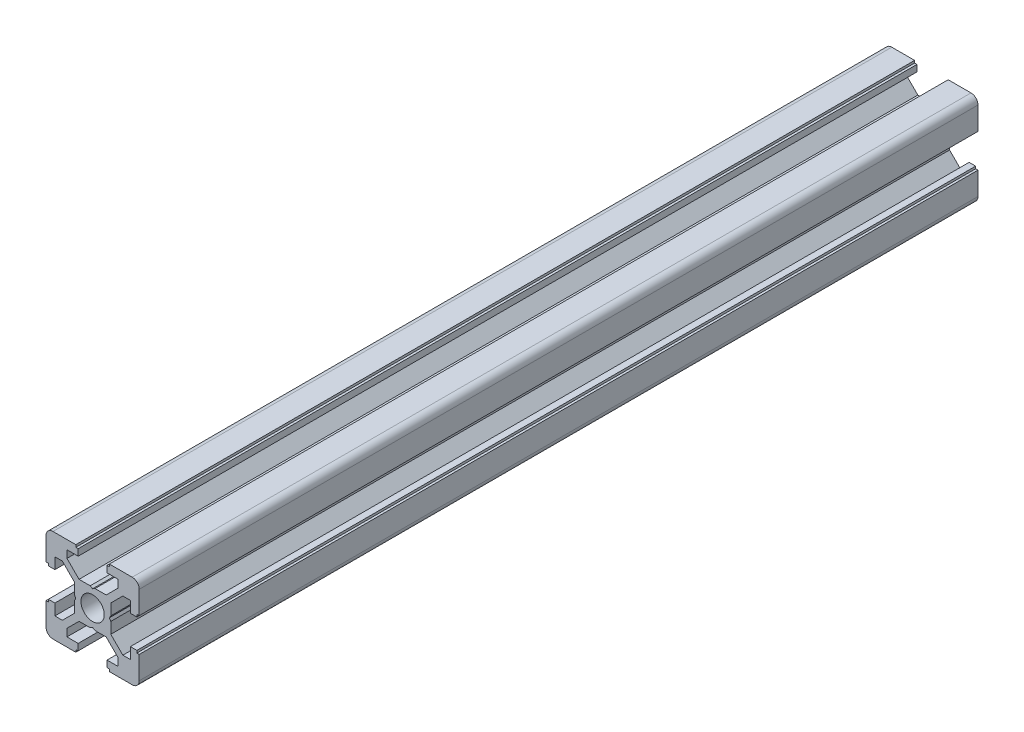
SolidWorks part; units mm, degrees
ref_plane "前视基准面" through (0, 0, 0) normal (0, 0, 1) x (1, 0, 0)
ref_plane "上视基准面" through (0, 0, 0) normal (0, 1, 0) x (1, 0, 0)
ref_plane "右视基准面" through (0, 0, 0) normal (1, 0, 0) x (0, 0, -1)
sketch "草图28" plane through (0, 0, 0) normal (0, 0, 1) x (1, 0, 0)
  line B0 (0, 11.0182) -> (0, -11.0182) construction
  line B1 (-11.0182, 0) -> (11.0182, 0) construction
  line B2 (-3.9, -0.5196) -> (-3.9, -2.9101)
  line B3 (-3.9, -2.9101) -> (-6.4899, -5.5)
  line B4 (-6.4899, -5.5) -> (-8.1, -5.5)
  line B5 (-8.1, -5.5) -> (-8.1, -3.1)
  line B6 (-8.1, -3.1) -> (-9.5, -3.1)
  line B7 (-9.5, -3.1) -> (-9.5, -3.6)
  line B8 (-9.5, -3.6) -> (-10, -3.6)
  line B9 (-10, -3.6) -> (-10, -8.5)
  line B10 (-8.5, -10) -> (-3.6, -10)
  line B11 (-3.6, -10) -> (-3.6, -9.5)
  line B12 (-3.6, -9.5) -> (-3.1, -9.5)
  line B13 (-3.1, -9.5) -> (-3.1, -8.1)
  line B14 (-3.1, -8.1) -> (-5.5, -8.1)
  line B15 (-5.5, -8.1) -> (-5.5, -6.4899)
  line B16 (-5.5, -6.4899) -> (-2.9101, -3.9)
  line B17 (-2.9101, -3.9) -> (-0.5196, -3.9)
  line B18 (-0.5196, -3.9) -> (0, -3.6)
  line B19 (0, -3.6) -> (0.5196, -3.9)
  line B20 (0.5196, -3.9) -> (2.9101, -3.9)
  line B21 (2.9101, -3.9) -> (5.5, -6.4899)
  line B22 (5.5, -6.4899) -> (5.5, -8.1)
  line B23 (5.5, -8.1) -> (3.1, -8.1)
  line B24 (3.1, -8.1) -> (3.1, -9.5)
  line B25 (3.1, -9.5) -> (3.6, -9.5)
  line B26 (3.6, -9.5) -> (3.6, -10)
  line B27 (3.6, -10) -> (8.5, -10)
  line B28 (10, -8.5) -> (10, -3.6)
  line B29 (10, -3.6) -> (9.5, -3.6)
  line B30 (9.5, -3.6) -> (9.5, -3.1)
  line B31 (9.5, -3.1) -> (8.1, -3.1)
  line B32 (8.1, -3.1) -> (8.1, -5.5)
  line B33 (8.1, -5.5) -> (6.4899, -5.5)
  line B34 (6.4899, -5.5) -> (3.9, -2.9101)
  line B35 (3.9, -2.9101) -> (3.9, -0.5196)
  line B36 (3.9, -0.5196) -> (3.6, 0)
  line B37 (3.6, 0) -> (3.9, 0.5196)
  line B38 (3.9, 0.5196) -> (3.9, 2.9101)
  line B39 (3.9, 2.9101) -> (6.4899, 5.5)
  line B40 (6.4899, 5.5) -> (8.1, 5.5)
  line B41 (8.1, 5.5) -> (8.1, 3.1)
  line B42 (8.1, 3.1) -> (9.5, 3.1)
  line B43 (9.5, 3.1) -> (9.5, 3.6)
  line B44 (9.5, 3.6) -> (10, 3.6)
  line B45 (10, 3.6) -> (10, 8.5)
  line B46 (8.5, 10) -> (3.6, 10)
  line B47 (3.6, 10) -> (3.6, 9.5)
  line B48 (3.6, 9.5) -> (3.1, 9.5)
  line B49 (3.1, 9.5) -> (3.1, 8.1)
  line B50 (3.1, 8.1) -> (5.5, 8.1)
  line B51 (5.5, 8.1) -> (5.5, 6.4899)
  line B52 (5.5, 6.4899) -> (2.9101, 3.9)
  line B53 (2.9101, 3.9) -> (0.5196, 3.9)
  line B54 (0.5196, 3.9) -> (0, 3.6)
  line B55 (0, 3.6) -> (-0.5196, 3.9)
  line B56 (-0.5196, 3.9) -> (-2.9101, 3.9)
  line B57 (-2.9101, 3.9) -> (-5.5, 6.4899)
  line B58 (-5.5, 6.4899) -> (-5.5, 8.1)
  line B59 (-5.5, 8.1) -> (-3.1, 8.1)
  line B60 (-3.1, 8.1) -> (-3.1, 9.5)
  line B61 (-3.1, 9.5) -> (-3.6, 9.5)
  line B62 (-3.6, 9.5) -> (-3.6, 10)
  line B63 (-3.6, 10) -> (-8.5, 10)
  line B64 (-10, 8.5) -> (-10, 3.6)
  line B65 (-10, 3.6) -> (-9.5, 3.6)
  line B66 (-9.5, 3.6) -> (-9.5, 3.1)
  line B67 (-9.5, 3.1) -> (-8.1, 3.1)
  line B68 (-8.1, 3.1) -> (-8.1, 5.5)
  line B69 (-8.1, 5.5) -> (-6.4899, 5.5)
  line B70 (-6.4899, 5.5) -> (-3.9, 2.9101)
  line B71 (-3.9, 2.9101) -> (-3.9, 0.5196)
  line B72 (-3.9, 0.5196) -> (-3.6, 0)
  line B73 (-3.6, 0) -> (-3.9, -0.5196)
  circle B74 centre (0, 0) radius 2.5
  arc B75 (-10, -8.5) -> (-8.5, -10) centre (-8.5, -8.5) ccw
  arc B76 (8.5, -10) -> (10, -8.5) centre (8.5, -8.5) ccw
  arc B77 (10, 8.5) -> (8.5, 10) centre (8.5, 8.5) ccw
  arc B78 (-8.5, 10) -> (-10, 8.5) centre (-8.5, 8.5) ccw
sketch_block_instance "块1-1"
sketch_block "块1"
extrude "凸台-拉伸1" add sketch "草图28" along normal blind 180
cosmetic thread "装饰螺纹线1" [suppressed] parameters "D1"=15, "D2"=6
cosmetic thread "装饰螺纹线2" [suppressed] parameters "D1"=15, "D2"=6
ref_plane "基准面1" through (0, 0, 180) normal (0, 0, 1) x (1, 0, 0)
ref_plane "基准面2" through (0, 10, 0) normal (0, 1, 0) x (1, 0, 0)
ref_plane "基准面3" through (0, -10, 0) normal (0, 1, 0) x (1, 0, 0)
ref_plane "基准面4" through (10, 0, 0) normal (1, 0, 0) x (0, 0, -1)
ref_plane "基准面5" through (-10, 0, 0) normal (1, 0, 0) x (0, 0, -1)
sketch "草图19" plane through (0, 0, 0) normal (0, 0, 1) x (1, 0, 0)
  line L0 (0, 0) -> (0, 11.6901) construction
  line L1 (0, 0) -> (10.3437, 0) construction
sketch "草图20" plane through (0, 0, 0) normal (0, 1, 0) x (1, 0, 0)
  line L0 (0, 0) -> (0, 3.5576) construction
ref_point "点1"
sketch "草图2" [suppressed] plane through (0, 0, 0) normal (1, 0, 0) x (0, 0, -1)
  line L0 (-280, -10) -> (-260, 10)
  line L1 (11, -10) -> (-11, -10) construction
  line L2 (11, 10) -> (-11, 10) construction
  line L3 (-260, 10) -> (-280, 10)
  line L4 (-280, 11) -> (-280, -11) construction
  line L5 (-280, 10) -> (-280, -10)
  dimension "D1" = 45
extrude "切除-拉伸1" [suppressed] cut sketch "草图2" against normal through all and the other way through all
sketch "草图3" [suppressed] plane through (0, 0, 0) normal (1, 0, 0) x (0, 0, -1)
  line L0 (0, -10) -> (-20, 10)
  line L1 (11, -10) -> (-11, -10) construction
  line L2 (11, 10) -> (-11, 10) construction
  line L3 (-20, 10) -> (0, 10)
  line L4 (0, 10) -> (0, -10)
  line L5 (0, 11) -> (0, -11) construction
  dimension "D1" = 45
extrude "切除-拉伸2" [suppressed] cut sketch "草图3" against normal through all and the other way through all
sketch "草图4" [suppressed] plane through (0, 0, 0) normal (1, 0, 0) x (0, 0, -1)
  line L0 (-280, 10) -> (-260, -10)
  line L1 (11, 10) -> (-11, 10) construction
  line L2 (-280, 11) -> (-280, -11) construction
  line L3 (11, -10) -> (-11, -10) construction
  line L4 (-260, -10) -> (-280, -10)
  line L5 (-280, -10) -> (-280, 10)
  dimension "D1" = 45
extrude "切除-拉伸3" [suppressed] cut sketch "草图4" against normal through all and the other way through all
sketch "草图5" [suppressed] plane through (0, 0, 0) normal (1, 0, 0) x (0, 0, -1)
  line L0 (0, 10) -> (-20, -10)
  line L1 (11, 10) -> (-11, 10) construction
  line L2 (11, -10) -> (-11, -10) construction
  line L3 (-20, -10) -> (0, -10)
  line L4 (0, -10) -> (0, 10)
  line L5 (0, 11) -> (0, -11) construction
  dimension "D1" = 45
extrude "切除-拉伸4" [suppressed] cut sketch "草图5" against normal through all and the other way through all
sketch "草图6" [suppressed] plane through (0, 0, 0) normal (0, 1, 0) x (1, 0, 0)
  line L0 (-10, -280) -> (10, -260)
  line L1 (-10, -11) -> (-10, 11) construction
  line L2 (-11, -280) -> (11, -280) construction
  line L3 (10, -11) -> (10, 11) construction
  line L4 (10, -260) -> (10, -280)
  line L5 (10, -280) -> (-10, -280)
  dimension "D1" = 45
extrude "切除-拉伸5" [suppressed] cut sketch "草图6" against normal through all and the other way through all
sketch "草图7" [suppressed] plane through (0, 0, 0) normal (0, 1, 0) x (1, 0, 0)
  line L0 (-10, 0) -> (10, -20)
  line L1 (-10, -11) -> (-10, 11) construction
  line L2 (10, -11) -> (10, 11) construction
  line L3 (10, -20) -> (10, 0)
  line L4 (-11, 0) -> (11, 0) construction
  line L5 (10, 0) -> (-10, 0)
  dimension "D1" = 45
extrude "切除-拉伸6" [suppressed] cut sketch "草图7" against normal through all and the other way through all
sketch "草图8" [suppressed] plane through (0, 0, 0) normal (0, 1, 0) x (1, 0, 0)
  line L0 (-10, -260) -> (10, -280)
  line L1 (-10, -11) -> (-10, 11) construction
  line L2 (10, -11) -> (10, 11) construction
  line L3 (-11, -280) -> (11, -280) construction
  line L4 (10, -280) -> (-10, -280)
  line L5 (-10, -280) -> (-10, -260)
  dimension "D1" = 45
extrude "切除-拉伸7" [suppressed] cut sketch "草图8" against normal through all and the other way through all
sketch "草图9" [suppressed] plane through (0, 0, 0) normal (0, 1, 0) x (1, 0, 0)
  line L0 (10, 0) -> (-10, -20)
  line L1 (10, -11) -> (10, 11) construction
  line L2 (-11, 0) -> (11, 0) construction
  line L3 (-10, -11) -> (-10, 11) construction
  line L4 (-10, -20) -> (-10, 0)
  line L5 (-10, 0) -> (10, 0)
  dimension "D1" = 45
extrude "切除-拉伸8" [suppressed] cut sketch "草图9" against normal through all and the other way through all
sketch "草图10" [suppressed] plane through (10, -3.64, 139.7) normal (1, 0, 0) x (0, 0, -1)
  line L1 (-140.3, 14.64) -> (-140.3, -7.36) construction
  circle A0 centre (-127.3, 3.64) radius 6.25
  dimension "D1" = 12.5
  dimension "D2" = 13
extrude "切除-拉伸9" [suppressed] cut sketch "草图10" against normal blind 9
sketch "草图11" [suppressed] plane through (10, 0, 0) normal (1, 0, 0) x (0, 0, -1)
  circle A0 centre (-13, 0) radius 6.25
  dimension "D1" = 12.5
  dimension "D2" = 13
extrude "切除-拉伸10" [suppressed] cut sketch "草图11" against normal blind 9
sketch "草图12" [suppressed] plane through (0, 0, 0) normal (0, 1, 0) x (1, 0, 0)
  line L0 (-10, -11) -> (-10, 11) construction
  line L1 (-10, -267) -> (-1, -267)
  line L2 (-10, -267) -> (-10, -260.75)
  line L3 (-10, -260.75) -> (-1, -260.75)
  line L4 (-1, -267) -> (-1, -260.75)
  line L5 (10, -11) -> (10, 11) construction
  line L6 (10, -267) -> (1, -267)
  line L7 (10, -267) -> (10, -260.75)
  line L8 (10, -260.75) -> (1, -260.75)
  line L9 (1, -267) -> (1, -260.75)
  line L10 (-11, -280) -> (11, -280) construction
  dimension "D1" = 13
  dimension "D2" = 6.25
  dimension "D3" = 9
revolve "切除-旋转1" [suppressed] cut sketch "草图12" angle 360 about L1
sketch "草图13" [suppressed] plane through (0, 0, 0) normal (0, 1, 0) x (1, 0, 0)
  line L0 (-10, -11) -> (-10, 11) construction
  line L1 (-10, -19.25) -> (-1, -19.25)
  line L2 (-10, -19.25) -> (-10, -13)
  line L3 (-10, -13) -> (-1, -13)
  line L4 (-1, -19.25) -> (-1, -13)
  line L5 (10, -11) -> (10, 11) construction
  line L6 (10, -19.25) -> (1, -19.25)
  line L7 (10, -19.25) -> (10, -13)
  line L8 (10, -13) -> (1, -13)
  line L9 (1, -19.25) -> (1, -13)
  dimension "D1" = 13
  dimension "D2" = 6.25
  dimension "D3" = 9
revolve "切除-旋转2" [suppressed] cut sketch "草图13" angle 360 about L3
sketch "草图14" [suppressed] plane through (0, 10, 0) normal (0, 1, 0) x (1, 0, 0)
  line L0 (-11, -280) -> (11, -280) construction
  circle A0 centre (0, -267) radius 6.25
  dimension "D1" = 12.5
  dimension "D2" = 13
extrude "切除-拉伸11" [suppressed] cut sketch "草图14" against normal blind 9
sketch "草图15" [suppressed] plane through (0, 10, 0) normal (0, 1, 0) x (1, 0, 0)
  line L0 (-11, 0) -> (11, 0) construction
  circle A0 centre (0, -13) radius 6.25
  dimension "D1" = 12.5
  dimension "D2" = 13
extrude "切除-拉伸12" [suppressed] cut sketch "草图15" against normal blind 9
sketch "草图16" [suppressed] plane through (0, 0, 0) normal (1, 0, 0) x (0, 0, -1)
  line L0 (11, 10) -> (-11, 10) construction
  line L1 (-267, 10) -> (-260.75, 10)
  line L2 (-267, 10) -> (-267, 1)
  line L3 (-267, 1) -> (-260.75, 1)
  line L4 (-260.75, 10) -> (-260.75, 1)
  line L5 (11, -10) -> (-11, -10) construction
  line L6 (-267, -10) -> (-260.75, -10)
  line L7 (-267, -10) -> (-267, -1)
  line L8 (-267, -1) -> (-260.75, -1)
  line L9 (-260.75, -10) -> (-260.75, -1)
  line L10 (-280, 11) -> (-280, -11) construction
  dimension "D1" = 9
  dimension "D2" = 6.25
  dimension "D3" = 13
revolve "切除-旋转3" [suppressed] cut sketch "草图16" angle 360 about L2
sketch "草图17" [suppressed] plane through (0, 0, 0) normal (1, 0, 0) x (0, 0, -1)
  line L0 (11, 10) -> (-11, 10) construction
  line L1 (-13, 10) -> (-19.25, 10)
  line L2 (-13, 10) -> (-13, 1)
  line L3 (-13, 1) -> (-19.25, 1)
  line L4 (-19.25, 10) -> (-19.25, 1)
  line L5 (11, -10) -> (-11, -10) construction
  line L6 (-13, -10) -> (-19.25, -10)
  line L7 (-13, -10) -> (-13, -1)
  line L8 (-13, -1) -> (-19.25, -1)
  line L9 (-19.25, -10) -> (-19.25, -1)
  dimension "D1" = 6.25
  dimension "D2" = 9
  dimension "D3" = 13
revolve "切除-旋转4" [suppressed] cut sketch "草图17" angle 360 about L2
sketch "草图18" [suppressed] plane through (0, 0, 0) normal (0, 1, 0) x (1, 0, 0)
  line L0 (-10, -230) -> (10, -230)
  line L1 (-10, -11) -> (-10, 11) construction
  line L2 (10, -11) -> (10, 11) construction
  line L3 (10, -230) -> (10, -224.5)
  line L4 (10, -224.5) -> (3.5, -224.5)
  line L5 (3.5, -224.5) -> (3.5, -226.75)
  line L6 (3.5, -226.75) -> (-10, -226.75)
  line L7 (-10, -226.75) -> (-10, -230)
  line L8 (-11, -280) -> (11, -280) construction
  dimension "D1" = 50
  dimension "D2" = 5.5
  dimension "D3" = 3.25
  dimension "D4" = 6.5
revolve "切除-旋转5" [suppressed] cut sketch "草图18" angle 360 about L0
other "表格阵列1" [suppressed] parameters "D0"=70, "D1"=0, "D2"=90, "D3"=0, "D4"=110, "D5"=0, "D6"=130, "D7"=0
sketch "草图21" [suppressed] plane through (0, 0, 0) normal (0, 1, 0) x (1, 0, 0)
  line L0 (-10, -50) -> (10, -50)
  line L1 (-10, -11) -> (-10, 11) construction
  line L2 (10, -11) -> (10, 11) construction
  line L3 (10, -50) -> (10, -55.5)
  line L4 (10, -55.5) -> (3.5, -55.5)
  line L5 (3.5, -55.5) -> (3.5, -53.25)
  line L6 (3.5, -53.25) -> (-10, -53.25)
  line L7 (-10, -53.25) -> (-10, -50)
  dimension "D1" = 5.5
  dimension "D2" = 3.25
  dimension "D3" = 6.5
  dimension "D4" = 50
revolve "切除-旋转6" [suppressed] cut sketch "草图21" angle 360 about L0
other "表格阵列2" [suppressed] parameters "D0"=70, "D1"=0, "D2"=90, "D3"=0, "D4"=110, "D5"=0, "D6"=130, "D7"=0
sketch "草图22" [suppressed] plane through (0, 0, 0) normal (1, 0, 0) x (0, 0, -1)
  line L0 (-230, 10) -> (-230, -10)
  line L1 (11, 10) -> (-11, 10) construction
  line L2 (11, -10) -> (-11, -10) construction
  line L3 (-230, -10) -> (-226.75, -10)
  line L4 (-226.75, -10) -> (-226.75, 3.5)
  line L5 (-226.75, 3.5) -> (-224.5, 3.5)
  line L6 (-224.5, 3.5) -> (-224.5, 10)
  line L7 (-224.5, 10) -> (-230, 10)
  line L8 (-280, 11) -> (-280, -11) construction
  dimension "D1" = 5.5
  dimension "D2" = 3.25
  dimension "D3" = 6.5
  dimension "D4" = 50
revolve "切除-旋转7" [suppressed] cut sketch "草图22" angle 360 about L0
other "表格阵列3" [suppressed] parameters "D0"=70, "D1"=0, "D2"=90, "D3"=0, "D4"=110, "D5"=0, "D6"=130, "D7"=0
sketch "草图23" [suppressed] plane through (0, 0, 0) normal (1, 0, 0) x (0, 0, -1)
  line L0 (-50, 10) -> (-55.5, 10)
  line L1 (11, 10) -> (-11, 10) construction
  line L2 (-55.5, 10) -> (-55.5, 3.5)
  line L3 (-55.5, 3.5) -> (-53.25, 3.5)
  line L4 (-53.25, 3.5) -> (-53.25, -10)
  line L5 (11, -10) -> (-11, -10) construction
  line L6 (-53.25, -10) -> (-50, -10)
  line L7 (-50, -10) -> (-50, 10)
  dimension "D1" = 5.5
  dimension "D2" = 3.25
  dimension "D3" = 6.5
  dimension "D4" = 50
revolve "切除-旋转8" [suppressed] cut sketch "草图23" angle 360 about L7
other "表格阵列4" [suppressed] parameters "D0"=70, "D1"=0, "D2"=90, "D3"=0, "D4"=110, "D5"=0, "D6"=130, "D7"=0
sketch "草图24" [suppressed] plane through (10, 0, 0) normal (1, 0, 0) x (0, 0, -1)
  line L0 (-280, 11) -> (-280, -11) construction
  circle A0 centre (-240, 0) radius 3.25
  dimension "D1" = 6.5
  dimension "D2" = 40
extrude "切除-拉伸13" [suppressed] cut sketch "草图24" against normal through all
other "表格阵列5" [suppressed] parameters "D0"=60, "D1"=0, "D2"=80, "D3"=0, "D4"=100, "D5"=0, "D6"=120, "D7"=0
sketch "草图25" [suppressed] plane through (10, 0, 0) normal (1, 0, 0) x (0, 0, -1)
  circle A0 centre (-40, 0) radius 3.25
  dimension "D1" = 6.5
  dimension "D2" = 40
extrude "切除-拉伸14" [suppressed] cut sketch "草图25" against normal through all
other "表格阵列6" [suppressed] parameters "D0"=60, "D1"=0, "D2"=80, "D3"=0, "D4"=100, "D5"=0, "D6"=120, "D7"=0
sketch "草图26" [suppressed] plane through (0, 10, 0) normal (0, 1, 0) x (1, 0, 0)
  line L0 (-11, -280) -> (11, -280) construction
  circle A0 centre (0, -240) radius 3.25
  dimension "D1" = 6.5
  dimension "D2" = 40
extrude "切除-拉伸15" [suppressed] cut sketch "草图26" against normal through all
other "表格阵列7" [suppressed] parameters "D0"=60, "D1"=0, "D2"=80, "D3"=0, "D4"=100, "D5"=0, "D6"=120, "D7"=0
sketch "草图27" [suppressed] plane through (0, 10, 0) normal (0, 1, 0) x (1, 0, 0)
  circle A0 centre (0, -40) radius 3.25
  dimension "D1" = 6.5
  dimension "D2" = 40
extrude "切除-拉伸16" [suppressed] cut sketch "草图27" against normal through all
other "表格阵列8" [suppressed] parameters "D0"=60, "D1"=0, "D2"=80, "D3"=0, "D4"=100, "D5"=0, "D6"=120, "D7"=0
sketch "草图29" [suppressed] plane through (0, 0, 0) normal (0, 1, 0) x (1, 0, 0)
  line L0 (-10, -230) -> (-10, -224.5)
  line L1 (-10, -224.5) -> (-3.5, -224.5)
  line L2 (-3.5, -224.5) -> (-3.5, -226.75)
  line L3 (-3.5, -226.75) -> (10, -226.75)
  line L4 (10, -226.75) -> (10, -230)
  line L5 (10, -230) -> (-10, -230)
  line L6 (-10, -11) -> (-10, 11) construction
  line L7 (10, -11) -> (10, 11) construction
  line L8 (-11, -280) -> (11, -280) construction
  dimension "D1" = 3.25
  dimension "D2" = 5.5
  dimension "D3" = 6.5
  dimension "D4" = 50
revolve "切除-旋转9" [suppressed] cut sketch "草图29" angle 360 about L5
other "表格阵列9" [suppressed] parameters "D0"=70, "D1"=0, "D2"=90, "D3"=0, "D4"=110, "D5"=0, "D6"=130, "D7"=0
sketch "草图30" [suppressed] plane through (0, 0, 0) normal (0, 1, 0) x (1, 0, 0)
  line L0 (10, -50) -> (10, -53.25)
  line L1 (10, -53.25) -> (-3.5, -53.25)
  line L2 (-3.5, -53.25) -> (-3.5, -55.5)
  line L3 (-3.5, -55.5) -> (-10, -55.5)
  line L4 (-10, -55.5) -> (-10, -50)
  line L5 (-10, -50) -> (10, -50)
  line L6 (-10, -11) -> (-10, 11) construction
  line L7 (10, -11) -> (10, 11) construction
  dimension "D1" = 5.5
  dimension "D2" = 6.5
  dimension "D3" = 3.25
  dimension "D4" = 50
revolve "切除-旋转10" [suppressed] cut sketch "草图30" angle 360 about L5
other "表格阵列10" [suppressed] parameters "D0"=70, "D1"=0, "D2"=90, "D3"=0, "D4"=110, "D5"=0, "D6"=130, "D7"=0
sketch "草图31" [suppressed] plane through (0, 0, 0) normal (1, 0, 0) x (0, 0, -1)
  line L0 (-230, 10) -> (-226.75, 10)
  line L1 (-226.75, 10) -> (-226.75, -3.5)
  line L2 (-226.75, -3.5) -> (-224.5, -3.5)
  line L3 (-224.5, -3.5) -> (-224.5, -10)
  line L4 (-224.5, -10) -> (-230, -10)
  line L5 (-230, -10) -> (-230, 10)
  line L6 (11, 10) -> (-11, 10) construction
  line L7 (11, -10) -> (-11, -10) construction
  line L8 (-280, 11) -> (-280, -11) construction
  dimension "D1" = 3.25
  dimension "D2" = 5.5
  dimension "D3" = 6.5
  dimension "D4" = 50
revolve "切除-旋转11" [suppressed] cut sketch "草图31" angle 360 about L5
other "表格阵列11" [suppressed] parameters "D0"=70, "D1"=0, "D2"=90, "D3"=0, "D4"=110, "D5"=0, "D6"=130, "D7"=0
sketch "草图32" [suppressed] plane through (0, 0, 0) normal (1, 0, 0) x (0, 0, -1)
  line L0 (-50, 10) -> (-53.25, 10)
  line L1 (-53.25, 10) -> (-53.25, -3.5)
  line L2 (-53.25, -3.5) -> (-55.5, -3.5)
  line L3 (-55.5, -3.5) -> (-55.5, -10)
  line L4 (-55.5, -10) -> (-50, -10)
  line L5 (-50, -10) -> (-50, 10)
  line L6 (11, 10) -> (-11, 10) construction
  line L7 (11, -10) -> (-11, -10) construction
  dimension "D1" = 3.25
  dimension "D2" = 5.5
  dimension "D3" = 6.5
  dimension "D4" = 50
revolve "切除-旋转12" [suppressed] cut sketch "草图32" angle 360 about L5
other "表格阵列12" [suppressed] parameters "D0"=70, "D1"=0, "D2"=90, "D3"=0, "D4"=110, "D5"=0, "D6"=130, "D7"=0
